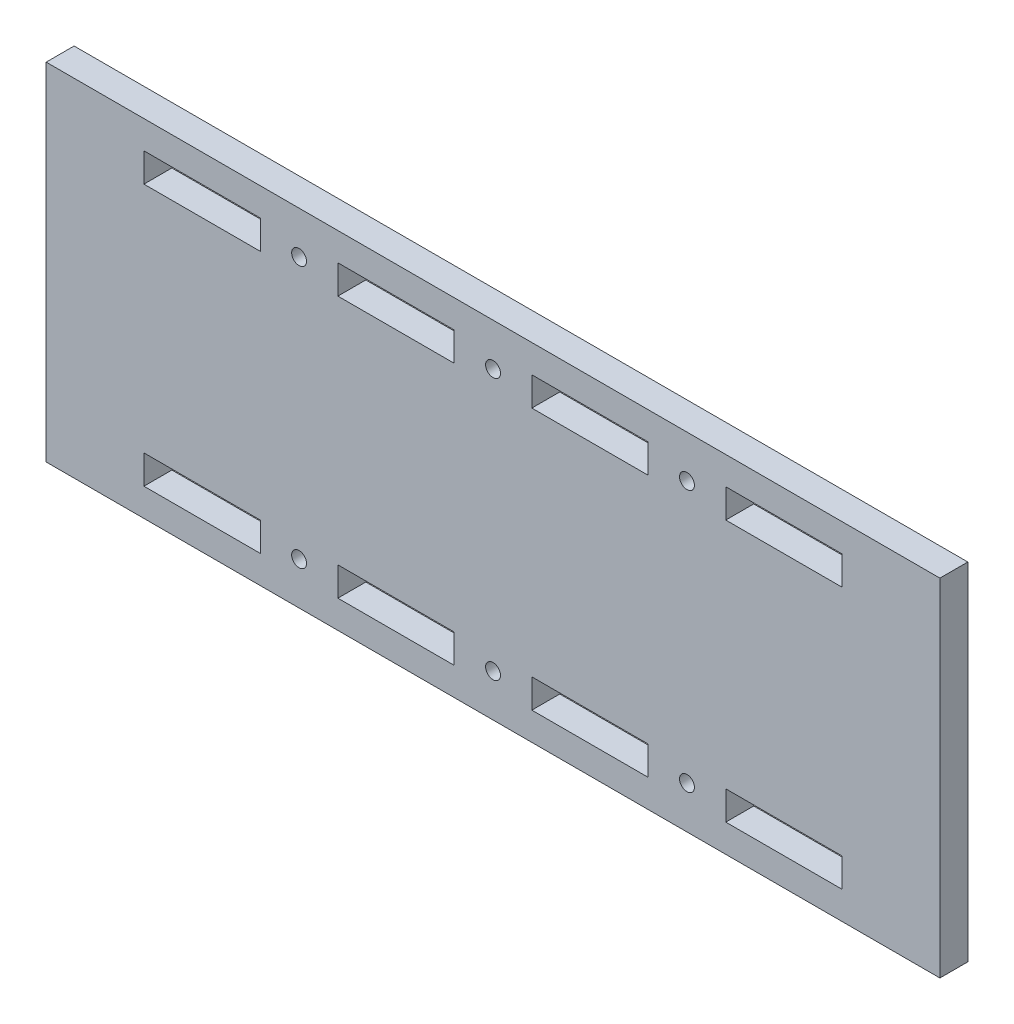
SolidWorks part; units mm, degrees
material "Oak"
ref_plane "Front Plane" through (0, 0, 0) normal (0, 0, 1) x (1, 0, 0)
ref_plane "Top Plane" through (0, 0, 0) normal (0, 1, 0) x (1, 0, 0)
ref_plane "Right Plane" through (0, 0, 0) normal (1, 0, 0) x (0, 0, -1)
sketch "Sketch1" plane through (0, 0, 0) normal (0, 0, 1) x (1, 0, 0)
  line L0 (-33.3333, -25) -> (-33.3333, -31.2)
  line L1 (-96, -37.2) -> (96, -37.2)
  line L2 (-96, -37.2) -> (-96, 37.2)
  line L3 (-96, 37.2) -> (96, 37.2)
  line L4 (96, -37.2) -> (96, 37.2)
  line L5 (-96, -37.2) -> (96, 37.2) construction
  line L6 (-96, 37.2) -> (96, -37.2) construction
  line L7 (-75, -25) -> (-50, -25)
  line L8 (-75, -25) -> (-75, -31.2)
  line L9 (-75, -31.2) -> (-50, -31.2)
  line L10 (-50, -25) -> (-50, -31.2)
  line L11 (-33.3333, -25) -> (-8.3333, -25)
  line L12 (-8.3333, -25) -> (-8.3333, -31.2)
  line L13 (-33.3333, -31.2) -> (-8.3333, -31.2)
  line L14 (8.3333, -25) -> (8.3333, -31.2)
  line L15 (8.3333, -25) -> (33.3333, -25)
  line L16 (33.3333, -25) -> (33.3333, -31.2)
  line L17 (8.3333, -31.2) -> (33.3333, -31.2)
  line L18 (50, -25) -> (50, -31.2)
  line L19 (50, -25) -> (75, -25)
  line L20 (75, -25) -> (75, -31.2)
  line L21 (50, -31.2) -> (75, -31.2)
  line L22 (-50, -28.1) -> (-33.3333, -28.1) construction
  line L23 (-8.3333, -28.1) -> (8.3333, -28.1) construction
  line L24 (-75, 31.2) -> (-75, 25)
  line L25 (-75, 31.2) -> (-50, 31.2)
  line L26 (-50, 31.2) -> (-50, 25)
  line L27 (-75, 25) -> (-50, 25)
  line L28 (-33.3333, 31.2) -> (-33.3333, 25)
  line L29 (-33.3333, 25) -> (-8.3333, 25)
  line L30 (-8.3333, 31.2) -> (-8.3333, 25)
  line L31 (-33.3333, 31.2) -> (-8.3333, 31.2)
  line L32 (8.3333, 31.2) -> (8.3333, 25)
  line L33 (8.3333, 25) -> (33.3333, 25)
  line L34 (33.3333, 31.2) -> (33.3333, 25)
  line L35 (8.3333, 31.2) -> (33.3333, 31.2)
  line L36 (50, 31.2) -> (50, 25)
  line L37 (50, 25) -> (75, 25)
  line L38 (75, 31.2) -> (75, 25)
  line L39 (50, 31.2) -> (75, 31.2)
  circle A10 centre (-41.6667, -28.1) radius 1.6
  circle A11 centre (0, -28.1) radius 1.6
  circle A12 centre (41.6667, -28.1) radius 1.6
  circle A13 centre (0, 28.1) radius 1.6
  circle A14 centre (41.6667, 28.1) radius 1.6
  circle A15 centre (-41.6667, 28.1) radius 1.6
  point P0 (0, 0)
  point P26 (0, -23.6)
  point P28 (-50, 28.1)
  point P62 (0, 0)
  dimension "D9" = 3.2
  dimension "D1" = 192
  dimension "D2" = 21
  dimension "D3" = 25
  dimension "D4" = 6
  dimension "D5" = 6.2
  dimension "D6" = 6
  dimension "D7" = 4
  dimension "D8" = 21
  dimension "D12" = 50
  dimension "D11" = 2
  dimension "D10" = 3
  dimension "D13" = 2
extrude "Boss-Extrude1" add sketch "Sketch1" along normal blind 6
